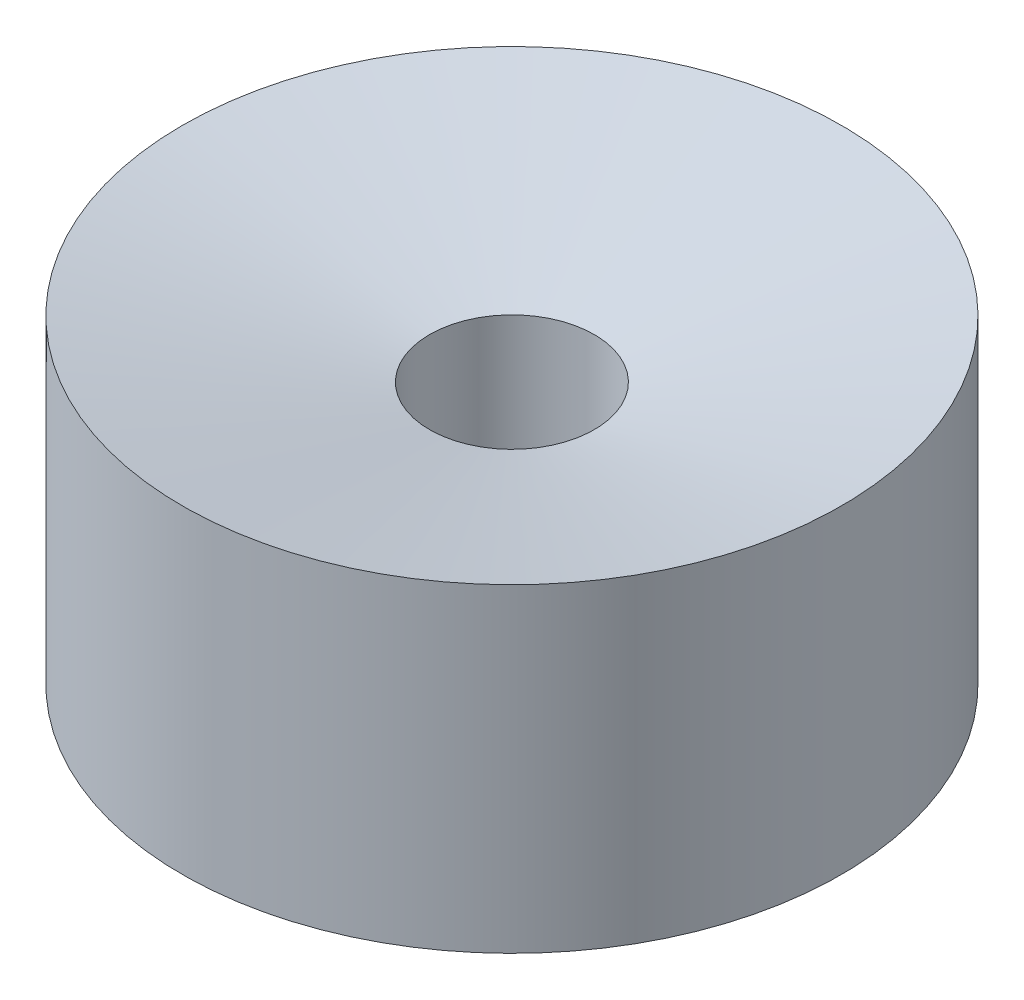
SolidWorks part; units mm, degrees
ref_plane "前视基准面" through (0, 0, 0) normal (0, 0, 1) x (1, 0, 0)
ref_plane "上视基准面" through (0, 0, 0) normal (0, 1, 0) x (1, 0, 0)
ref_plane "右视基准面" through (0, 0, 0) normal (1, 0, 0) x (0, 0, -1)
sketch "草图1" plane through (0, 0, 0) normal (0, 0, 1) x (1, 0, 0)
  line L0 (0, 0) -> (0.7, 0)
  line L1 (0.7, 0) -> (0.7, 0.8197)
  line L2 (0.7, 0.8197) -> (1.14, 0.8197)
  line L3 (1.14, 0.5197) -> (1.14, -0.33)
  line L4 (1.14, -0.33) -> (1.6, -0.33)
  line L5 (1.6, -0.33) -> (1.6, 1.22)
  line L6 (1.6, 1.22) -> (0.4, 0.9406)
  line L7 (0.4, 0.9406) -> (0.4, 0.15)
  line L8 (0.4, 0.15) -> (0, 0.15)
  line L9 (0, 0.15) -> (0, 0)
  line L10 (1.14, 0.8197) -> (1.28, 0.8197)
  line L11 (1.28, 0.8197) -> (1.28, 0.5197)
  line L12 (1.28, 0.5197) -> (1.14, 0.5197)
  point P13 (0, 0.075)
  point P16 (0.7174, 0.8197)
  dimension "D1" = 1.6
  dimension "D2" = 0.46
  dimension "D3" = 0.7
  dimension "D4" = 1.22
  dimension "D5" = 1.2
  dimension "D6" = 0.15
  dimension "D7" = 1.55
  dimension "D8" = 1.28
  dimension "D9" = 0.3
revolve "旋转1" add sketch "草图1" angle 360 about L9
sketch "草图2" plane through (0, 0.15, 0) normal (0, 1, 0) x (1, 0, 0)
  circle A0 centre (0, 0) radius 0.275
  dimension "D1" = 0.55
extrude "切除-拉伸1" cut sketch "草图2" against normal up to next
